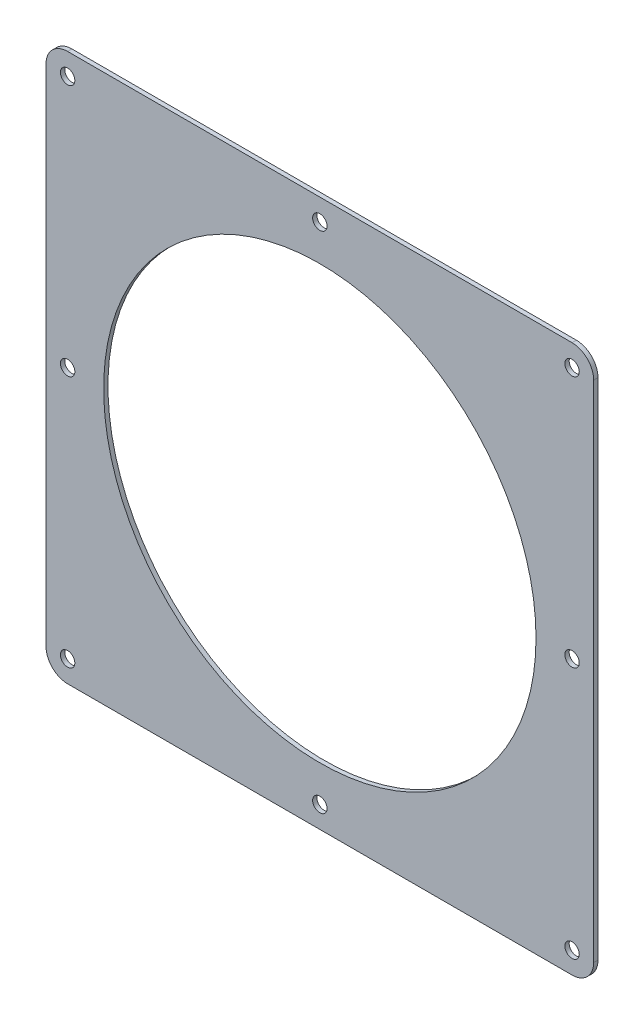
SolidWorks part; units mm, degrees
ref_plane "Front Plane" through (0, 0, 0) normal (0, 0, 1) x (1, 0, 0)
ref_plane "Top Plane" through (0, 0, 0) normal (0, 1, 0) x (1, 0, 0)
ref_plane "Right Plane" through (0, 0, 0) normal (1, 0, 0) x (0, 0, -1)
sketch "Sketch2" plane through (0, 0, 0) normal (0, 0, 1) x (1, 0, 0)
  line L0 (-175, 175) -> (175, 175) construction
  line L1 (-175, 190) -> (175, 190)
  line L2 (-190, 175) -> (-190, -175)
  line L3 (-175, -190) -> (175, -190)
  line L4 (190, 175) -> (190, -175)
  line L5 (-190, 190) -> (190, -190) construction
  line L6 (-190, -190) -> (190, 190) construction
  line L7 (175, 175) -> (175, -175) construction
  line L8 (175, -175) -> (-175, -175) construction
  line L9 (-175, -175) -> (-175, 175) construction
  line L15 (-150, 150) -> (150, -150) construction
  line L16 (-150, -150) -> (150, 150) construction
  arc A0 (-190, -175) -> (-175, -190) centre (-175, -175) ccw
  arc A1 (175, -190) -> (190, -175) centre (175, -175) ccw
  arc A2 (175, 190) -> (190, 175) centre (175, 175) cw
  arc A3 (-175, 190) -> (-190, 175) centre (-175, 175) ccw
  circle A4 centre (-175, 175) radius 5
  circle A5 centre (0, 175) radius 5
  circle A6 centre (175, 175) radius 5
  circle A14 centre (175, 0) radius 5
  circle A15 centre (-175, 0) radius 5
  circle A16 centre (-175, -175) radius 5
  circle A17 centre (0, -175) radius 5
  circle A18 centre (175, -175) radius 5
  circle A19 centre (0, 0) radius 150
  point P0 (0, 0)
  point P26 (0, 0)
  dimension "D3" = 15
  dimension "D4" = 10
  dimension "D5" = 10
  dimension "D6" = 10
  dimension "D7" = 300
  dimension "D8" = 10
  dimension "D9" = 10
  dimension "D10" = 10
  dimension "D11" = 10
  dimension "D12" = 300
  dimension "D1" = 380
  dimension "D2" = 380
extrude "Boss-Extrude1" add sketch "Sketch2" along normal blind 3
